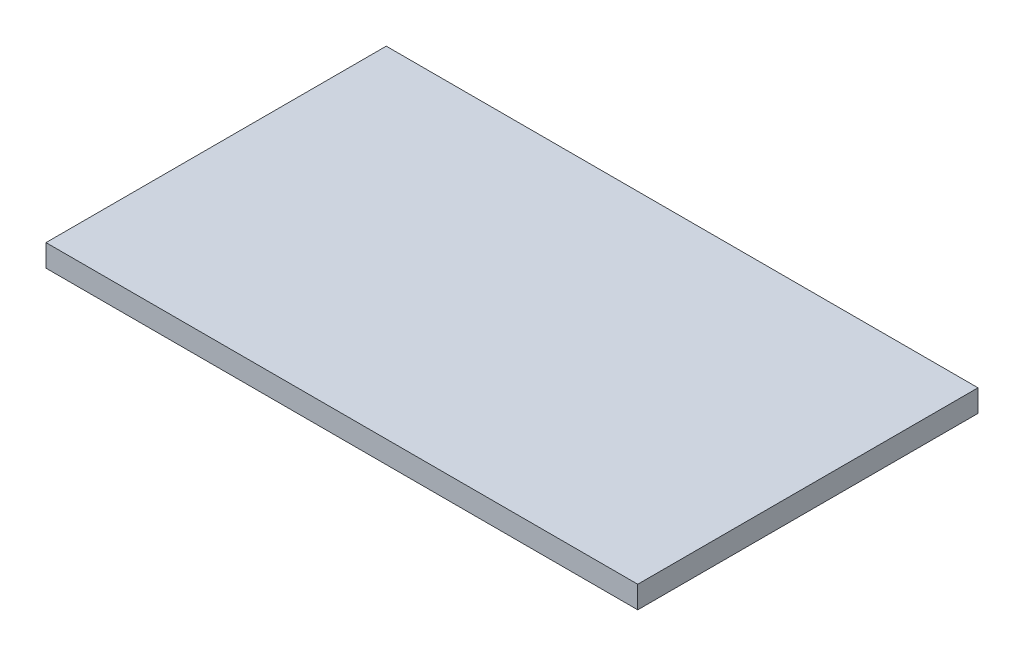
SolidWorks part; units mm, degrees
ref_plane "Front Plane" through (0, 0, 0) normal (0, 0, 1) x (1, 0, 0)
ref_plane "Top Plane" through (0, 0, 0) normal (0, 1, 0) x (1, 0, 0)
ref_plane "Right Plane" through (0, 0, 0) normal (1, 0, 0) x (0, 0, -1)
sketch "Sketch1" plane through (0, 0, 0) normal (0, 1, 0) x (1, 0, 0)
  line L1 (0, 0) -> (508, 0)
  line L2 (0, 0) -> (0, 292.1)
  line L3 (0, 292.1) -> (508, 292.1)
  line L4 (508, 0) -> (508, 292.1)
  dimension "D1" = 508
  dimension "D2" = 292.1
extrude "Boss-Extrude1" add sketch "Sketch1" along normal blind 19.05
